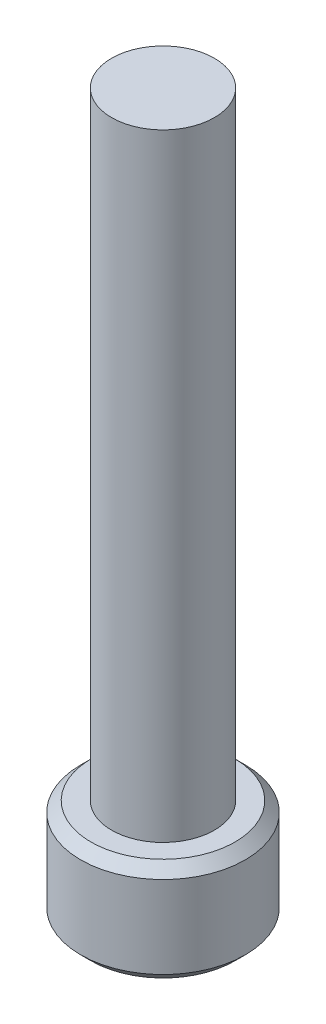
SolidWorks part; units mm, degrees
ref_plane "Front Plane" through (0, 0, 0) normal (0, 0, 1) x (1, 0, 0)
ref_plane "Top Plane" through (0, 0, 0) normal (0, 1, 0) x (1, 0, 0)
ref_plane "Right Plane" through (0, 0, 0) normal (1, 0, 0) x (0, 0, -1)
sketch "Sketch1" plane through (0, 0, 0) normal (0, 1, 0) x (1, 0, 0)
  circle A0 centre (0, 0) radius 2.5
extrude "Boss-Extrude1" add sketch "Sketch1" along normal blind 30
sketch "Sketch3" plane through (0, 0, 0) normal (0, 0, 1) x (1, 0, 0)
  line L0 (0, 0) -> (-4, 0)
  line L1 (-2.5, 0) -> (2.5, 0) construction
  line L2 (-4, 0) -> (-4, -5)
  line L3 (0, 0) -> (0, 12.6087) construction
  line L4 (-4, -5) -> (0, -5)
  line L5 (0, -5) -> (0, 0)
revolve "Revolve1" add sketch "Sketch3" angle 360 about L5
sketch "Sketch4" plane through (0, 0, 0) normal (0, 1, 0) x (1, 0, 0)
  line L1 (2.8868, 0) -> (1.4434, 2.5)
  line L2 (1.4434, 2.5) -> (-1.4434, 2.5)
  line L3 (-1.4434, 2.5) -> (-2.8868, 0)
  line L4 (-2.8868, 0) -> (-1.4434, -2.5)
  line L5 (-1.4434, -2.5) -> (1.4434, -2.5)
  line L6 (1.4434, -2.5) -> (2.8868, 0)
  circle A0 centre (0, 0) radius 2.5 construction
extrude "Cut-Extrude1" cut sketch "Sketch4" against normal blind 30 from offset 1 offset against normal yes
chamfer "Chamfer1" distance 0.5 angle 45 2 edges at (0, -5, -4) (0, 0, -4)
